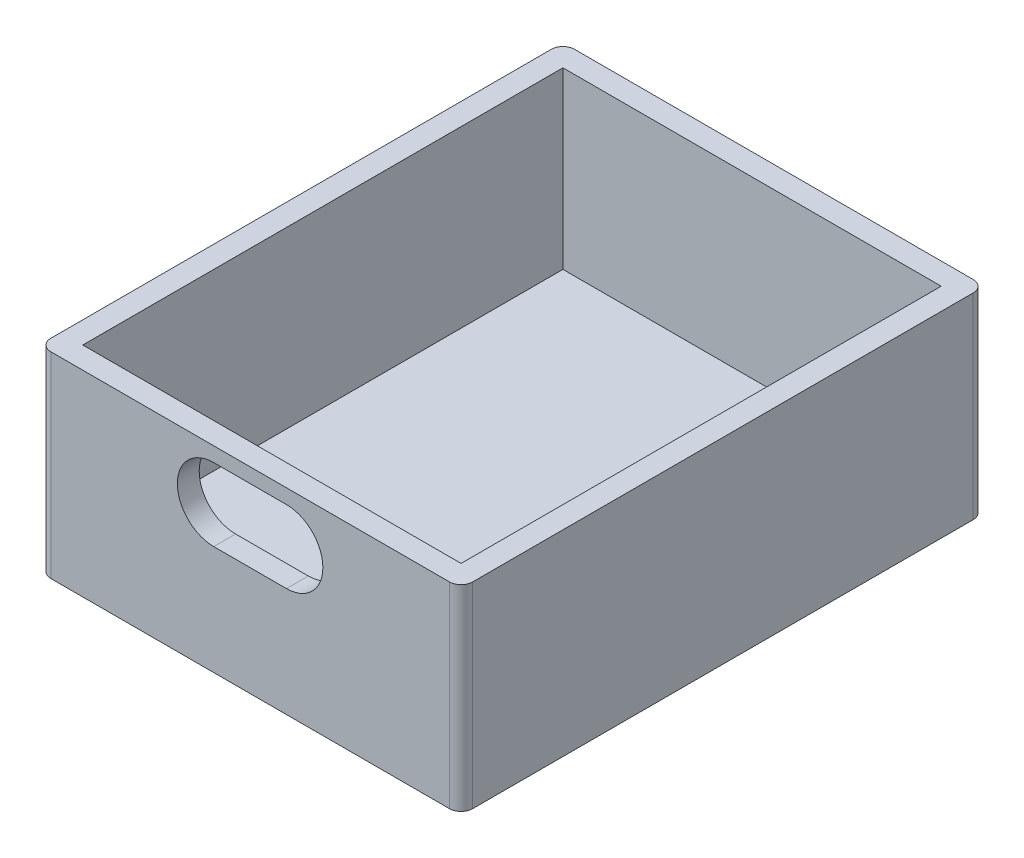
SolidWorks part; units mm, degrees
other "Markup1"
sketch "Sketch4" plane through (29, 0, 36) normal (0.3487, 0.4411, 0.8269) x (0.8274, -0.5594, -0.0504)
ref_plane "Front Plane" through (0, 0, 0) normal (0, 0, 1) x (1, 0, 0)
ref_plane "Top Plane" through (0, 0, 0) normal (0, 1, 0) x (1, 0, 0)
ref_plane "Right Plane" through (0, 0, 0) normal (1, 0, 0) x (0, 0, -1)
sketch "Sketch1" plane through (0, 0, 0) normal (0, 0, 1) x (1, 0, 0)
  line L1 (0, 0) -> (29, 0)
  line L2 (0, 0) -> (0, -13.5)
  line L3 (0, -13.5) -> (29, -13.5)
  line L4 (29, 0) -> (29, -13.5)
  dimension "D1" = 29
  dimension "D2" = 13.5
extrude "Boss-Extrude1" add sketch "Sketch1" along normal blind 36
sketch "Sketch2" plane through (0, 0, 0) normal (0, 1, 0) x (1, 0, 0)
  line L0 (0, -36) -> (0, 0) construction
  line L1 (1.5, -1.5) -> (27.5, -1.5)
  line L2 (1.5, -1.5) -> (1.5, -34.5)
  line L3 (1.5, -34.5) -> (27.5, -34.5)
  line L4 (27.5, -1.5) -> (27.5, -34.5)
  line L5 (29, -36) -> (29, 0) construction
  line L6 (29, 0) -> (0, 0) construction
  line L7 (29, -36) -> (0, -36) construction
  dimension "D1" = 1.5
  dimension "D2" = 1.5
  dimension "D3" = 1.5
  dimension "D4" = 1.5
extrude "Cut-Extrude1" cut sketch "Sketch2" against normal blind 12
sketch "Sketch3" plane through (0, 0, 36) normal (0, 0, 1) x (1, 0, 0)
  line L0 (12, -1) -> (17, -1)
  line L1 (12, -6) -> (17, -6)
  line L2 (0, -13.5) -> (29, -13.5) construction
  line L4 (29, -13.5) -> (29, 0) construction
  arc A3 (12, -6) -> (12, -1) centre (12, -3.5) cw
  arc A4 (17, -6) -> (17, -1) centre (17, -3.5) ccw
  dimension "D1" = 2.5
  dimension "D4" = 2.5
  dimension "D6" = 2.5
  dimension "D2" = 5
  dimension "D3" = 5
  dimension "D5" = 7.5
  dimension "D7" = 5
  dimension "D8" = 12
extrude "Cut-Extrude2" cut sketch "Sketch3" against normal up to surface (1.5 mm away) contours A3 L0 A4 L1 up to face at (14.5, -6, 34.5)
fillet "Fillet1" radius 0.8 4 edges at (0, -6.75, 36) (0, -6.75, 0) (29, -6.75, 0) (29, -6.75, 36)
sketch "Sketch5" plane through (0, -13.5, 0) normal (0, -1, 0) x (1, 0, 0)
  line L0 (0, 35.2) -> (0, 0.8) construction
  line L1 (22, 10) -> (18, 10)
  line L2 (22, 10) -> (22, 18)
  line L3 (22, 18) -> (18, 18)
  line L4 (18, 10) -> (18, 18)
  line L5 (8, 10) -> (4, 10)
  line L6 (8, 10) -> (8, 18)
  line L7 (8, 18) -> (4, 18)
  line L8 (4, 10) -> (4, 18)
  line L9 (0.8, 0) -> (28.2, 0) construction
  dimension "D1" = 4
  dimension "D2" = 8
  dimension "D3" = 4
  dimension "D4" = 8
  dimension "D5" = 10
  dimension "D6" = 4
  dimension "D7" = 10
  dimension "D8" = 10
extrude "Boss-Extrude2" add sketch "Sketch5" along normal blind 3.5
sketch "Sketch6" plane through (4, 0, 0) normal (-1, 0, 0) x (0, 0, 1)
  line L5 (18, -13.5) -> (10, -13.5) construction
  line L6 (13, -13.5) -> (18, -13.5)
  line L7 (13, -13.5) -> (13, -15)
  line L8 (13, -15) -> (18, -15)
  line L9 (18, -13.5) -> (18, -15)
  line L10 (18, -17) -> (18, -13.5) construction
  dimension "D1" = 1.5
  dimension "D2" = 5
extrude "Cut-Extrude3" cut sketch "Sketch6" against normal up to surface (18 mm away) up to face at (22, -15.25, 14)
